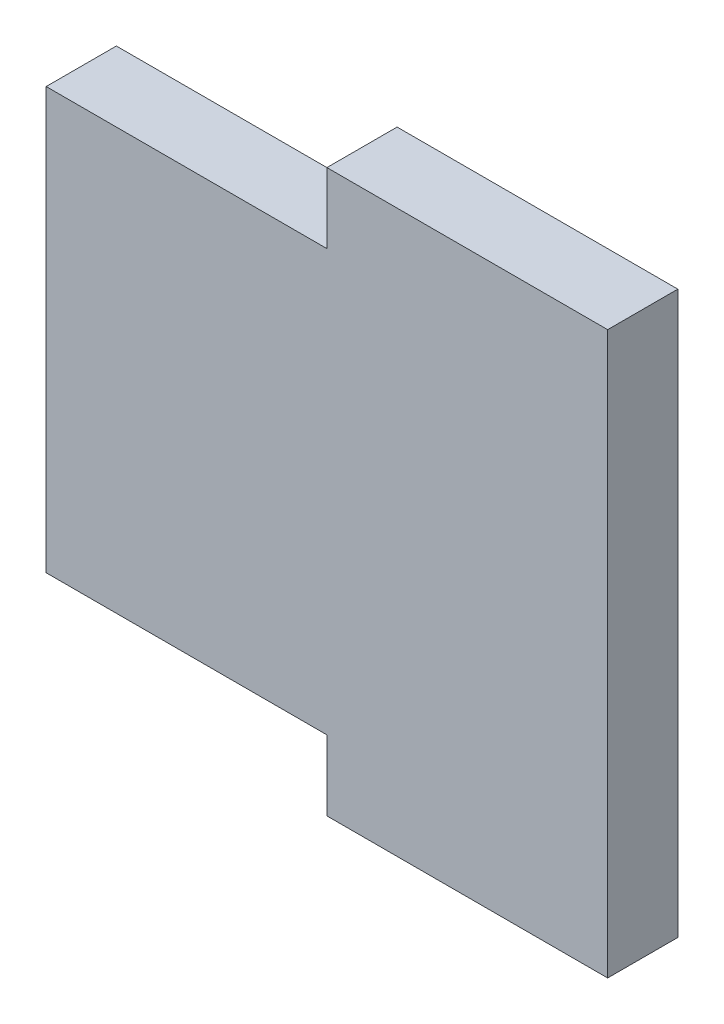
SolidWorks part; units mm, degrees
ref_plane "Front Plane" through (0, 0, 0) normal (0, 0, 1) x (1, 0, 0)
ref_plane "Top Plane" through (0, 0, 0) normal (0, 1, 0) x (1, 0, 0)
ref_plane "Right Plane" through (0, 0, 0) normal (1, 0, 0) x (0, 0, -1)
sketch "Sketch1" plane through (0, 0, 0) normal (0, 0, 1) x (1, 0, 0)
  line L1 (250.6005, 0) -> (237.9005, 0)
  line L2 (250.6005, 0) -> (250.6005, -25.4)
  line L3 (250.6005, -25.4) -> (237.9005, -25.4)
  line L4 (225.2005, -3.175) -> (225.2005, -22.225)
  line L7 (225.2005, -3.175) -> (237.9005, -3.175)
  line L8 (237.9005, 0) -> (237.9005, -3.175)
  line L11 (225.2005, -22.225) -> (237.9005, -22.225)
  line L12 (237.9005, -25.4) -> (237.9005, -22.225)
extrude "Boss-Extrude1" add sketch "Sketch1" along normal blind 3.175 contours L2 L3 L12 L11 L4 L7 L8 L1
